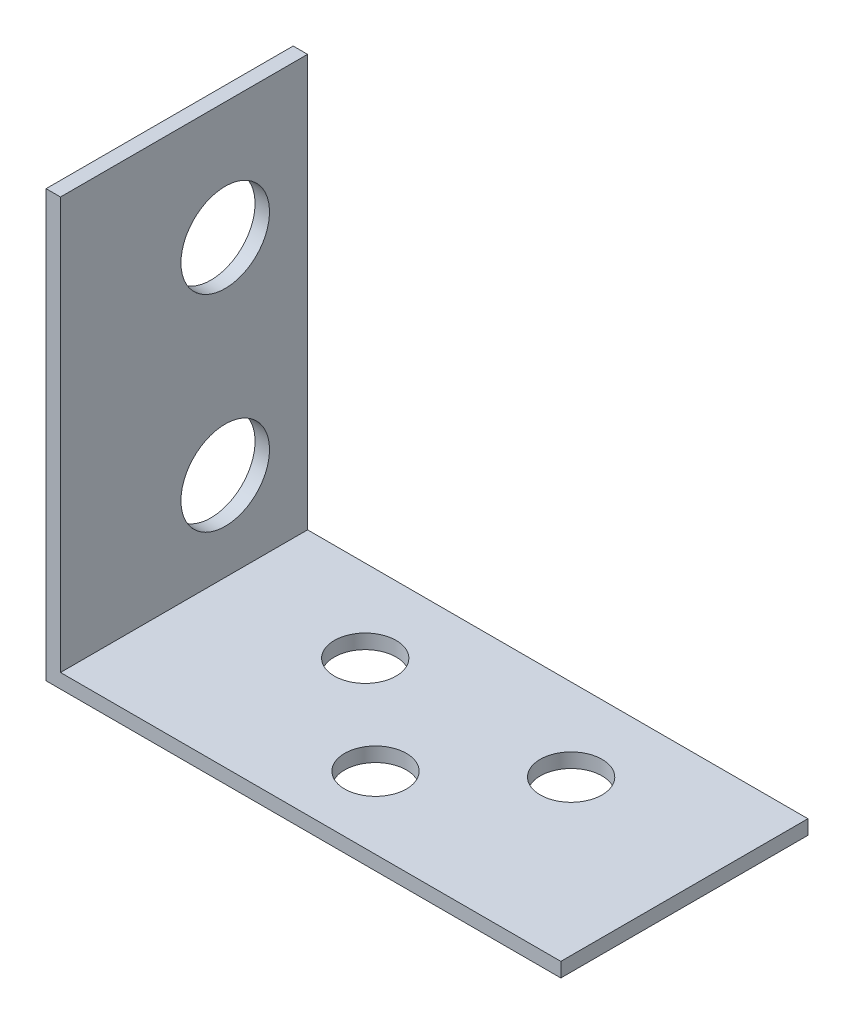
SolidWorks part; units mm, degrees
ref_plane "Front Plane" through (0, 0, 0) normal (0, 0, 1) x (1, 0, 0)
ref_plane "Top Plane" through (0, 0, 0) normal (0, 1, 0) x (1, 0, 0)
ref_plane "Right Plane" through (0, 0, 0) normal (1, 0, 0) x (0, 0, -1)
sketch "Sketch1" plane through (0, 0, 0) normal (0, 1, 0) x (1, 0, 0)
  line L0 (-12.5, 8) -> (12.5, 8) construction
  line L1 (-12.5, 12) -> (12.5, 12)
  line L2 (-12.5, 12) -> (-12.5, 0)
  line L3 (-12.5, 0) -> (12.5, 0)
  line L4 (12.5, 12) -> (12.5, 0)
  line L5 (0, 12) -> (0, 0) construction
  circle A0 centre (-5, 8) radius 1.5
  circle A1 centre (5, 8) radius 1.5
  circle A2 centre (0, 3.5) radius 1.5
  point P4 (0, 0)
  dimension "D3" = 3
  dimension "D1" = 12
  dimension "D2" = 25
  dimension "D4" = 7.5
  dimension "D5" = 4
  dimension "D6" = 3.5
extrude "Boss-Extrude1" add sketch "Sketch1" along normal blind 0.7 contours L0 L2 L3 L5 A0 | L0 L5 L3 L4 A1 | L5 L0 A1 L4 L1 | L2 L0 A0 L5 L1
sketch "Sketch3" plane through (0, 0.7, 0) normal (0, 1, 0) x (1, 0, 0)
  line L0 (-12.5, 0) -> (12.5, 0) construction
  line L1 (-12.5, 0) -> (-11.8, 0)
  line L2 (-12.5, 0) -> (-12.5, 12)
  line L3 (-12.5, 12) -> (-11.8, 12)
  line L4 (-11.8, 0) -> (-11.8, 12)
  line L5 (-12.5, 12) -> (-12.5, 0) construction
  point P8 (-20, 10)
  point P10 (-20, 12.6)
  point P11 (20, 0)
  point P12 (20, 0)
  dimension "D1" = 0.7
extrude "Boss-Extrude3" add sketch "Sketch3" along normal blind 20
sketch "Sketch4" plane through (-12.5, 0, 0) normal (-1, 0, 0) x (0, 0, 1)
  line L0 (-8, 20.7) -> (-8, 0) construction
  line L1 (-12, 20.7) -> (0, 20.7) construction
  line L2 (-12, 0) -> (0, 0) construction
  circle A0 centre (-8, 5) radius 2.15
  circle A1 centre (-8, 15) radius 2.15
  dimension "D4" = 4.3
  dimension "D1" = 4
  dimension "D2" = 5
  dimension "D3" = 10
extrude "Cut-Extrude1" cut sketch "Sketch4" against normal through all
